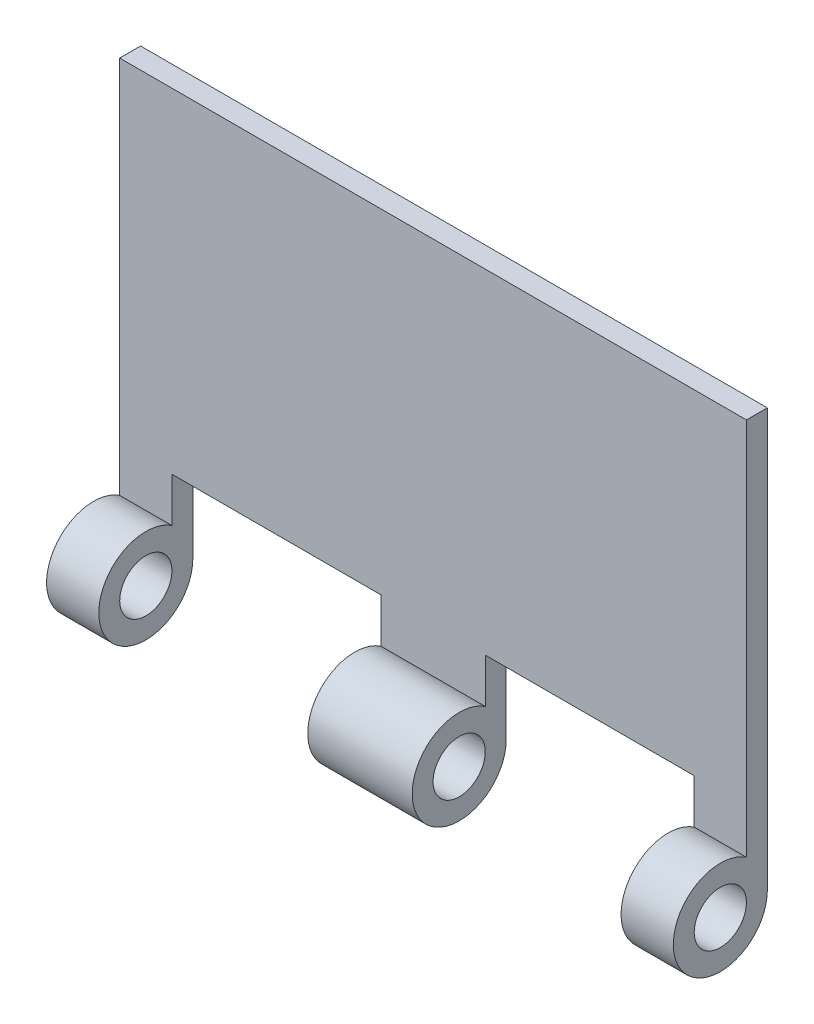
SolidWorks part; units mm, degrees
ref_plane "Front" through (0, 0, 0) normal (0, 0, 1) x (1, 0, 0)
ref_plane "Top" through (0, 0, 0) normal (0, 1, 0) x (1, 0, 0)
ref_plane "Right" through (0, 0, 0) normal (1, 0, 0) x (0, 0, -1)
sketch "Sketch1" plane through (0, 0, 0) normal (0, 0, 1) x (1, 0, 0)
  line L1 (0, 0) -> (-76.2, 0)
  line L2 (0, 0) -> (0, 50.8)
  line L3 (0, 50.8) -> (-76.2, 50.8)
  line L4 (-76.2, 0) -> (-76.2, 50.8)
  dimension "D1" = 76.2
  dimension "D2" = 50.8
extrude "Boss-Extrude1" add sketch "Sketch1" along normal blind 2.54
sketch "Sketch2" plane through (-76.2, 0, 0) normal (-1, 0, 0) x (0, 0, 1)
  line L0 (0, 50.8) -> (0, 0) construction
  circle A0 centre (5.715, 0) radius 5.715
  circle A1 centre (5.715, 0) radius 3.175
  point P3 (10.395, -7.1454)
  dimension "D1" = 2.54
  dimension "D2" = 6.35
extrude "Boss-Extrude2" add sketch "Sketch2" against normal up to surface (76.2 mm away) up to face at (0, 25.4, 1.27)
sketch "Sketch3" plane through (0, 0, 0) normal (0, 0, -1) x (-1, 0, 0)
  line L0 (76.2, 0) -> (0, 0) construction
  line L1 (6.35, 10.16) -> (31.75, 10.16)
  line L2 (6.35, 10.16) -> (6.35, -15.24)
  line L3 (6.35, -15.24) -> (31.75, -15.24)
  line L4 (31.75, 10.16) -> (31.75, -15.24)
  line L5 (44.45, 10.16) -> (69.85, 10.16)
  line L6 (44.45, 10.16) -> (44.45, -15.24)
  line L7 (44.45, -15.24) -> (69.85, -15.24)
  line L8 (69.85, 10.16) -> (69.85, -15.24)
  line L9 (0, 0) -> (0, 50.8) construction
  line L10 (76.2, 50.8) -> (76.2, 0) construction
  dimension "D1" = 25.4
  dimension "D2" = 10.16
  dimension "D3" = 10.16
  dimension "D4" = 25.4
  dimension "D5" = 25.4
  dimension "D6" = 25.4
  dimension "D7" = 6.35
  dimension "D8" = 6.35
extrude "Cut-Extrude1" cut sketch "Sketch3" against normal through all
